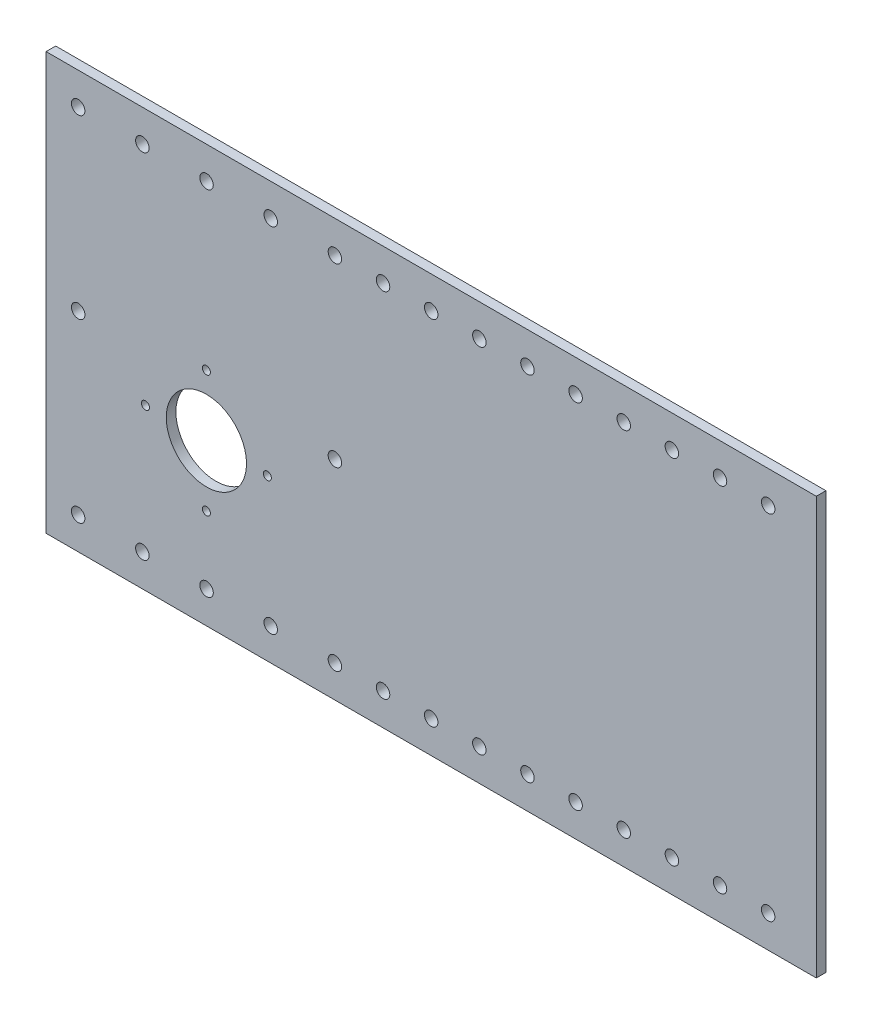
SolidWorks part; units mm, degrees
material "黑玻纤板"
ref_plane "前视基准面" through (0, 0, 0) normal (0, 0, 1) x (1, 0, 0)
ref_plane "上视基准面" through (0, 0, 0) normal (0, 1, 0) x (1, 0, 0)
ref_plane "右视基准面" through (0, 0, 0) normal (1, 0, 0) x (0, 0, -1)
sketch "草图1" plane through (0, 0, 0) normal (0, 0, 1) x (1, 0, 0)
  line L1 (-50, 65) -> (50, 65)
  line L2 (-50, 65) -> (-50, -65)
  line L3 (-50, -65) -> (50, -65)
  line L4 (50, 65) -> (50, -65)
  line L5 (-50, 65) -> (50, -65) construction
  line L6 (-50, -65) -> (50, 65) construction
  point P0 (0, 0)
  dimension "D1" = 100
  dimension "D2" = 130
extrude "凸台-拉伸1" add sketch "草图1" along normal blind 3
sketch "草图2" plane through (0, 0, 3) normal (0, 0, 1) x (1, 0, 0)
  line L0 (50, 55) -> (-50, 55) construction
  line L1 (50, -65) -> (50, 65) construction
  line L2 (-50, 65) -> (-50, -65) construction
  line L3 (50, 65) -> (-50, 65) construction
  line L4 (-40, 65) -> (-40, -65) construction
  line L5 (-50, -65) -> (50, -65) construction
  line L6 (0, 65) -> (0, -65) construction
  line L7 (40, 65) -> (40, -65) construction
  line L8 (50, 0) -> (-50, 0) construction
  line L9 (50, -55) -> (-50, -55) construction
  circle A0 centre (-40, 55) radius 2.1
  circle A1 centre (-20, 55) radius 2.1
  circle A2 centre (0, 55) radius 2.1
  circle A3 centre (20, 55) radius 2.1
  circle A4 centre (40, 55) radius 2.1
  circle A5 centre (-40, 0) radius 2.1
  circle A6 centre (-40, -55) radius 2.1
  circle A7 centre (-40, -110) radius 2.1
  circle A8 centre (-40, -165) radius 2.1
  circle A9 centre (-40, -220) radius 2.1
  circle A10 centre (-40, -275) radius 2.1
  circle A11 centre (-40, -330) radius 2.1
  circle A12 centre (-40, -385) radius 2.1
  circle A13 centre (40, -385) radius 2.1
  circle A14 centre (40, -330) radius 2.1
  circle A15 centre (40, -275) radius 2.1
  circle A16 centre (40, -220) radius 2.1
  circle A17 centre (40, -165) radius 2.1
  circle A18 centre (40, -110) radius 2.1
  circle A19 centre (40, -55) radius 2.1
  circle A20 centre (40, 0) radius 2.1
  circle A21 centre (40, 55) radius 2.1
  circle A22 centre (20, -55) radius 2.1
  circle A23 centre (0, -55) radius 2.1
  circle A24 centre (-20, -55) radius 2.1
  dimension "D3" = 4.2
  dimension "D4" = 20
  dimension "D7" = 20
  dimension "D1" = 10
  dimension "D2" = 10
  dimension "D5" = 20
  dimension "D6" = 20
  dimension "D8" = 9
extrude "切除-拉伸1" cut sketch "草图2" against normal through all contours A24 | A12 | A11 | A23 | A22 | A13 | A14 | A15 | A10 | A9 | A8 | A16 | A17 | A18 | A19 | A20 | A3 | A2 | A1 | A0 | A5 | A7 | A6 | A4
sketch "草图3" plane through (0, 0, 0) normal (0, 0, -1) x (-1, 0, 0)
  line L0 (0, 65) -> (0, -65) construction
  line L1 (-50, 65) -> (50, 65) construction
  line L2 (50, -65) -> (-50, -65) construction
  circle A0 centre (0.0422, -15) radius 19 construction
  circle A1 centre (19.0422, -15) radius 1.25
  circle A2 centre (0.0422, -34) radius 1.25
  circle A3 centre (-18.9578, -15) radius 1.25
  circle A4 centre (0.0422, 4) radius 1.25
  point P20 (0.0422, -15)
  dimension "D1" = 38
  dimension "D2" = 2.5
  dimension "D4" = 50
  dimension "D3" = 4
extrude "切除-拉伸2" cut sketch "草图3" against normal through all both and the other way through all
sketch "草图4" plane through (0, 0, 0) normal (0, 0, -1) x (-1, 0, 0)
  line L0 (20.2922, -15) -> (-20.2078, -15) construction
  line L1 (0.0422, 5.25) -> (0.0422, -35.25) construction
  circle A0 centre (0.0422, -15) radius 12.5
  circle A1 centre (0.0422, -15) radius 19 construction
  circle A2 centre (19.0422, -15) radius 1.25 construction
  circle A3 centre (-18.9578, -15) radius 1.25 construction
  circle A4 centre (0.0422, 4) radius 1.25 construction
  circle A5 centre (0.0422, -34) radius 1.25 construction
  dimension "D1" = 25
extrude "切除-拉伸3" cut sketch "草图4" against normal through all both and the other way through all
sketch "草图5" plane through (0, 0, 3) normal (0, 0, 1) x (1, 0, 0)
  line L0 (50, 65) -> (-50, 65) construction
  line L1 (50, -65) -> (190, -65)
  line L2 (50, -65) -> (50, 65)
  line L3 (50, 65) -> (190, 65)
  line L4 (190, -65) -> (190, 65)
  point P7 (168.34, 63.34)
  dimension "D1" = 140
extrude "凸台-拉伸2" add sketch "草图5" against normal up to surface (3 mm away) up to face at (12.4578, -15, 0)
sketch "草图6" plane through (0, 0, 3) normal (0, 0, 1) x (1, 0, 0)
  line L0 (-40, 55) -> (190, 55) construction
  line L1 (190, -65) -> (190, 65) construction
  line L2 (190, 0) -> (-50, 0) construction
  line L3 (-50, 65) -> (-50, -65) construction
  line L4 (-40, -55) -> (190, -55) construction
  circle A0 centre (55, 55) radius 2.1
  circle A4 centre (40, 55) radius 2.1 construction
  circle A5 centre (70, 55) radius 2.1
  circle A6 centre (85, 55) radius 2.1
  circle A7 centre (100, 55) radius 2.1
  circle A8 centre (115, 55) radius 2.1
  circle A9 centre (130, 55) radius 2.1
  circle A10 centre (145, 55) radius 2.1
  circle A11 centre (145, -55) radius 2.1
  circle A12 centre (130, -55) radius 2.1
  circle A13 centre (115, -55) radius 2.1
  circle A14 centre (100, -55) radius 2.1
  circle A15 centre (85, -55) radius 2.1
  circle A16 centre (70, -55) radius 2.1
  circle A17 centre (55, -55) radius 2.1
  circle A18 centre (160, -55) radius 2.1
  circle A19 centre (175, -55) radius 2.1
  circle A20 centre (160, 55) radius 2.1
  circle A21 centre (175, 55) radius 2.1
  dimension "D1" = 15
  dimension "D2" = 7
  dimension "D3" = 3
extrude "切除-拉伸4" cut sketch "草图6" against normal through all both and the other way through all
